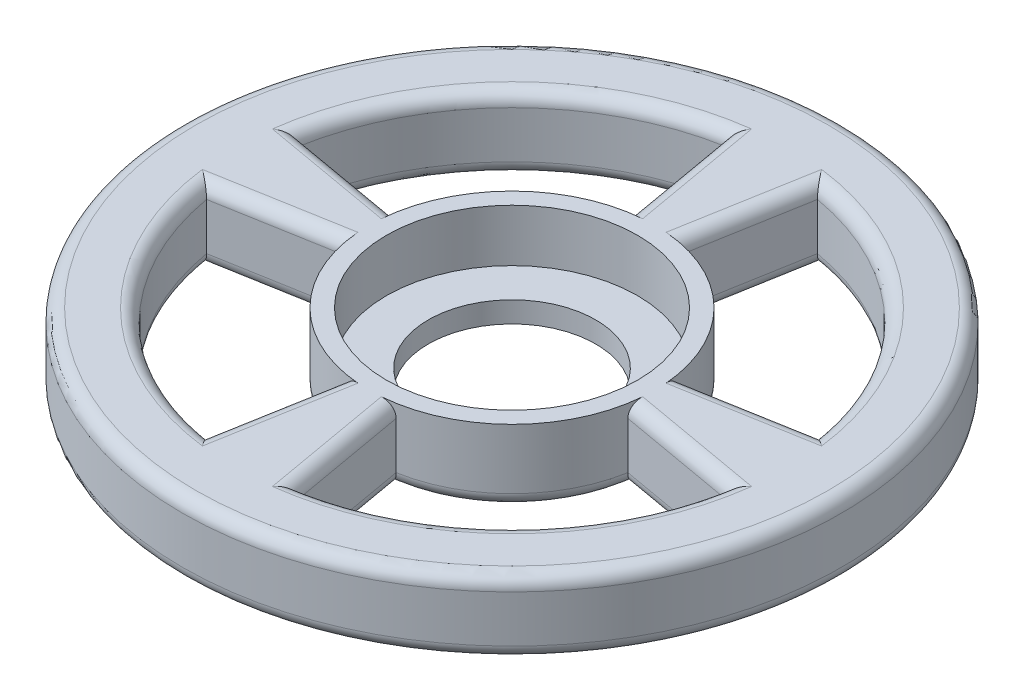
SolidWorks part; units mm, degrees
ref_plane "Front Plane" through (0, 0, 0) normal (0, 0, 1) x (1, 0, 0)
ref_plane "Top Plane" through (0, 0, 0) normal (0, 1, 0) x (1, 0, 0)
ref_plane "Right Plane" through (0, 0, 0) normal (1, 0, 0) x (0, 0, -1)
sketch "Sketch1" plane through (0, 0, 0) normal (0, 1, 0) x (1, 0, 0)
  circle A0 centre (0, 0) radius 6.35
  circle A1 centre (0, 0) radius 25
  dimension "D1" = 12.7
  dimension "D2" = 50
extrude "Boss-Extrude1" add sketch "Sketch1" along normal blind 5.5562
sketch "Sketch2" plane through (0, 5.5562, 0) normal (0, 1, 0) x (1, 0, 0)
  circle A0 centre (0, 0) radius 9.525
extrude "Cut-Extrude1" cut sketch "Sketch2" against normal blind 3.9688
sketch "Sketch3" plane through (0, 5.5562, 0) normal (0, 1, 0) x (1, 0, 0)
  line L0 (-1.8822, 10.6744) -> (-3.473, 19.6962)
  line L1 (1.8822, 10.6744) -> (3.473, 19.6962)
  line L2 (10.6744, -1.8822) -> (19.6962, -3.473)
  line L3 (10.6744, 1.8822) -> (19.6962, 3.473)
  line L4 (-1.8822, -10.6744) -> (-3.473, -19.6962)
  line L5 (1.8822, -10.6744) -> (3.473, -19.6962)
  line L6 (-10.6744, 1.8822) -> (-19.6962, 3.473)
  line L7 (-10.6744, -1.8822) -> (-19.6962, -3.473)
  arc A0 (-1.8822, 10.6744) -> (-10.6744, 1.8822) centre (0, 0) ccw
  arc A2 (-3.473, 19.6962) -> (-19.6962, 3.473) centre (0, 0) ccw
  arc A3 (10.6744, 1.8822) -> (1.8822, 10.6744) centre (0, 0) ccw
  arc A4 (19.6962, 3.473) -> (3.473, 19.6962) centre (0, 0) ccw
  arc A7 (3.473, -19.6962) -> (19.6962, -3.473) centre (0, 0) ccw
  arc A8 (1.8822, -10.6744) -> (10.6744, -1.8822) centre (0, 0) ccw
  arc A9 (-10.6744, -1.8822) -> (-1.8822, -10.6744) centre (0, 0) ccw
  arc A10 (-19.6962, -3.473) -> (-3.473, -19.6962) centre (0, 0) ccw
  point P23 (0, 0)
  dimension "D2" = 20
  dimension "D1" = 4
extrude "Cut-Extrude2" cut sketch "Sketch3" against normal through all
fillet "Fillet2" radius 1 30 edges at (0, 0, 25) (0, 5.5562, 25) (15.1853, 0, 2.6776) (-2.6776, 0, 15.1853) (-14.1421, 0, 14.1421) (-15.1853, 0, 2.6776) (2.6776, 0, -15.1853) (14.1421, 0, -14.1421) (15.1853, 0, -2.6776) (14.1421, 0, 14.1421) (2.6776, 0, 15.1853) (7.6644, 0, 7.6644) (-7.6644, 0, 7.6644) (7.6644, 0, -7.6644) (-7.6644, 0, -7.6644) (-2.6776, 0, -15.1853) (-15.1853, 0, -2.6776) (-14.1421, 0, -14.1421) (2.6776, 5.5562, -15.1853) (14.1421, 5.5562, -14.1421) (15.1853, 5.5562, -2.6776) (15.1853, 5.5562, 2.6776) (14.1421, 5.5562, 14.1421) (2.6776, 5.5562, 15.1853) (-2.6776, 5.5562, 15.1853) (-14.1421, 5.5562, 14.1421) (-15.1853, 5.5562, 2.6776) (-14.1421, 5.5562, -14.1421) (-15.1853, 5.5562, -2.6776) (-2.6776, 5.5562, -15.1853)
